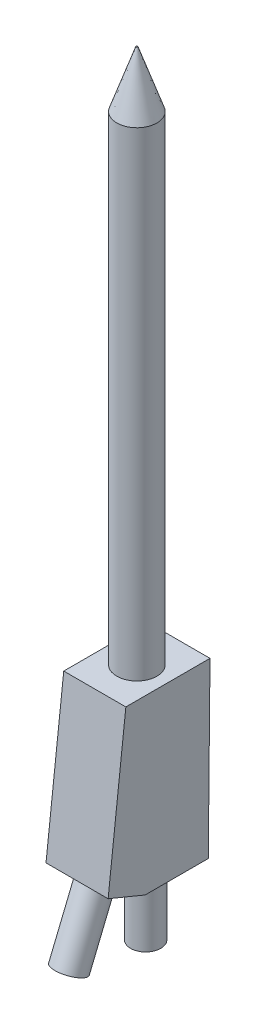
SolidWorks part; units mm, degrees
ref_plane "Ebene vorne" through (0, 0, 0) normal (0, 0, 1) x (1, 0, 0)
ref_plane "Ebene oben" through (0, 0, 0) normal (0, 1, 0) x (1, 0, 0)
ref_plane "Ebene rechts" through (0, 0, 0) normal (1, 0, 0) x (0, 0, -1)
sketch "Sketch1" plane through (0, 0, 0) normal (0, 1, 0) x (1, 0, 0)
  circle A0 centre (0, 0) radius 2
  dimension "D1" = 4
extrude "Boss-Extrude1" add sketch "Sketch1" along normal blind 50
sketch "Sketch2" plane through (0, 0, 0) normal (0, 0, 1) x (1, 0, 0)
  line L0 (0, 55.6) -> (0, 50)
  line L1 (0, 50) -> (2, 50)
  line L2 (0, 55.6) -> (0.0785, 55.6)
  line L3 (0.0785, 55.6) -> (2, 50)
  line L4 (2, 50) -> (-2, 50) construction
  line L5 (-2, 50) -> (2, 50) construction
  point P8 (0, 50)
  dimension "D1" = 5.6
revolve "Revolve1" add sketch "Sketch2" angle 360 about L0
sketch "Sketch3" plane through (0, 0, 0) normal (1, 0, 0) x (0, 0, -1)
  line L0 (-4.2, 2.1715) -> (4.2, 2.1715)
  line L1 (4.2, 2.1715) -> (4.0299, -15.0483)
  line L2 (4.0299, -15.0483) -> (-2.2701, -15.0483)
  line L3 (-2.2701, -15.0483) -> (-5.9701, -13.5285)
  line L4 (-5.9701, -13.5285) -> (-4.2, 2.1715)
  line L5 (0, 2.1715) -> (0, -22.4515) construction
  point P7 (0, 0)
  point P8 (-3.6192, -14.4176)
  point P10 (0, 0)
  dimension "D1" = 15.7
  dimension "D2" = 8.4
  dimension "D3" = 10
  dimension "D4" = 4
  dimension "D5" = 6.3
extrude "Boss-Extrude2" add sketch "Sketch3" along normal mid plane 6.2
sketch "Sketch4" plane through (0, -13.6736, 5.6168) normal (0, -0.925, 0.38) x (-1, 0, 0)
  line L0 (3.1, 1.618) -> (-3.1, 1.618) construction
  line L1 (3.1, -0.382) -> (3.1, 3.618) construction
  line L2 (-3.1, -0.382) -> (-3.1, 3.618) construction
  line L3 (0, -0.382) -> (0, 3.618) construction
  line L4 (-3.1, -0.382) -> (3.1, -0.382) construction
  line L5 (-3.1, 3.618) -> (3.1, 3.618) construction
  circle A0 centre (0, 1.618) radius 1.5
  point P14 (0, 0)
  dimension "D1" = 3
extrude "Boss-Extrude3" add sketch "Sketch4" along normal blind 7 contours A0
sketch "Sketch5" plane through (0, -15.0483, 0) normal (0, -1, 0) x (-1, 0, 0)
  line L0 (0, 4.0299) -> (0, -2.2701) construction
  line L1 (-3.1, 4.0299) -> (3.1, 4.0299) construction
  line L2 (-3.1, -2.2701) -> (3.1, -2.2701) construction
  line L3 (3.1, 0.8799) -> (-3.1, 0.8799) construction
  line L4 (3.1, -2.2701) -> (3.1, 4.0299) construction
  line L5 (-3.1, -2.2701) -> (-3.1, 4.0299) construction
  circle A0 centre (0, 0.8799) radius 1.5
  point P14 (0, 0)
  point P15 (0, 0.8799)
  dimension "D1" = 3
extrude "Boss-Extrude4" add sketch "Sketch5" along normal blind 7
